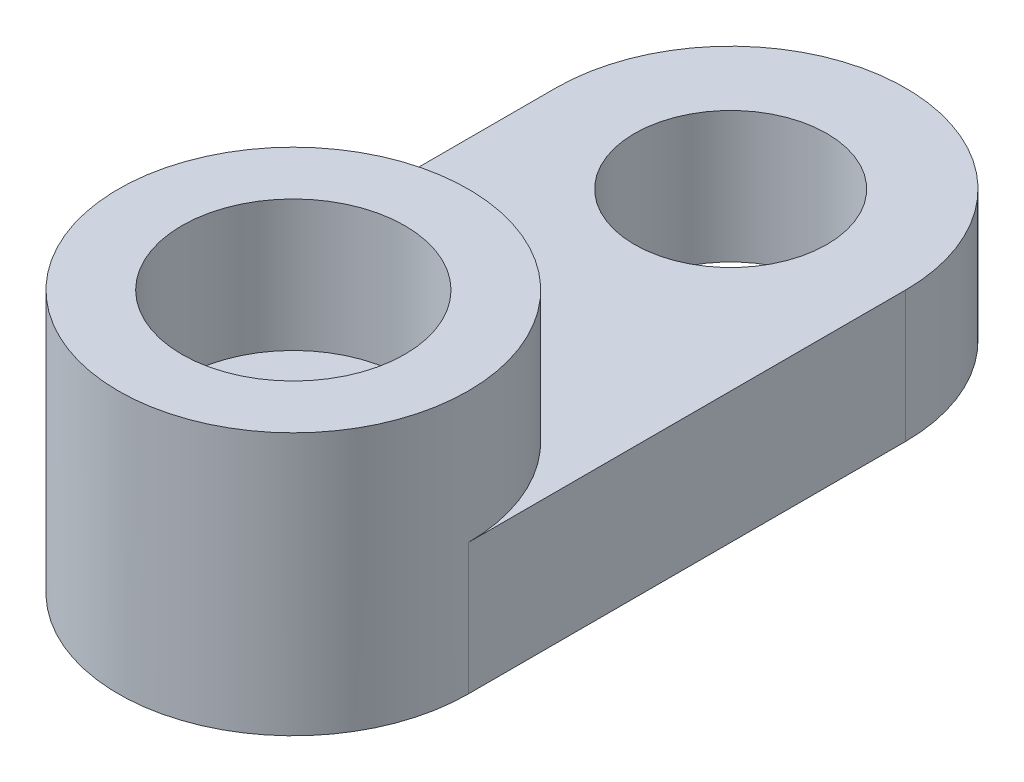
SolidWorks part; units mm, degrees
ref_plane "Front Plane" through (0, 0, 0) normal (0, 0, 1) x (1, 0, 0)
ref_plane "Top Plane" through (0, 0, 0) normal (0, 1, 0) x (1, 0, 0)
ref_plane "Right Plane" through (0, 0, 0) normal (1, 0, 0) x (0, 0, -1)
sketch "Sketch1" plane through (0, 0, 0) normal (0, 1, 0) x (1, 0, 0)
  line L0 (0, 0) -> (0, 12.7) construction
  line L1 (-5.08, 0) -> (-5.08, 12.7)
  line L2 (5.08, 0) -> (5.08, 12.7)
  circle A0 centre (0, 0) radius 1.778
  arc A1 (-5.08, 0) -> (5.08, 0) centre (0, 0) ccw
  arc A2 (5.08, 12.7) -> (-5.08, 12.7) centre (0, 12.7) ccw
  circle A3 centre (0, 12.7) radius 2.794
  point P3 (0, 6.35)
  dimension "D1" = 3.556
  dimension "D2" = 12.7
  dimension "D3" = 10.16
  dimension "D4" = 5.588
extrude "base" add sketch "Sketch1" along normal blind 3.81
sketch "Sketch2" plane through (0, 3.81, 0) normal (0, 1, 0) x (1, 0, 0)
  circle A0 centre (0, 0) radius 5.08
  arc A1 (-5.08, 0) -> (5.08, 0) centre (0, 0) ccw construction
  circle A2 centre (0, 0) radius 3.2385
  dimension "D1" = 6.477
extrude "Boss-Extrude2" add sketch "Sketch2" along normal blind 3.81
